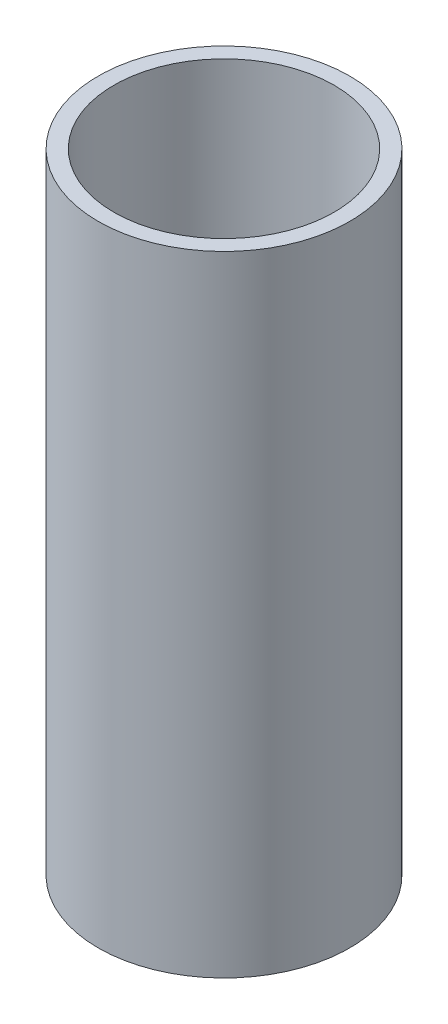
SolidWorks part; units mm, degrees
ref_plane "Front Plane" through (0, 0, 0) normal (0, 0, 1) x (1, 0, 0)
ref_plane "Top Plane" through (0, 0, 0) normal (0, 1, 0) x (1, 0, 0)
ref_plane "Right Plane" through (0, 0, 0) normal (1, 0, 0) x (0, 0, -1)
sketch "Sketch1" plane through (0, 0, 0) normal (0, 1, 0) x (1, 0, 0)
  circle A0 centre (0, 0) radius 40
  circle A1 centre (0, 0) radius 35
  dimension "D1" = 5
  dimension "D2" = 80
extrude "Boss-Extrude1" add sketch "Sketch1" along normal blind 200
